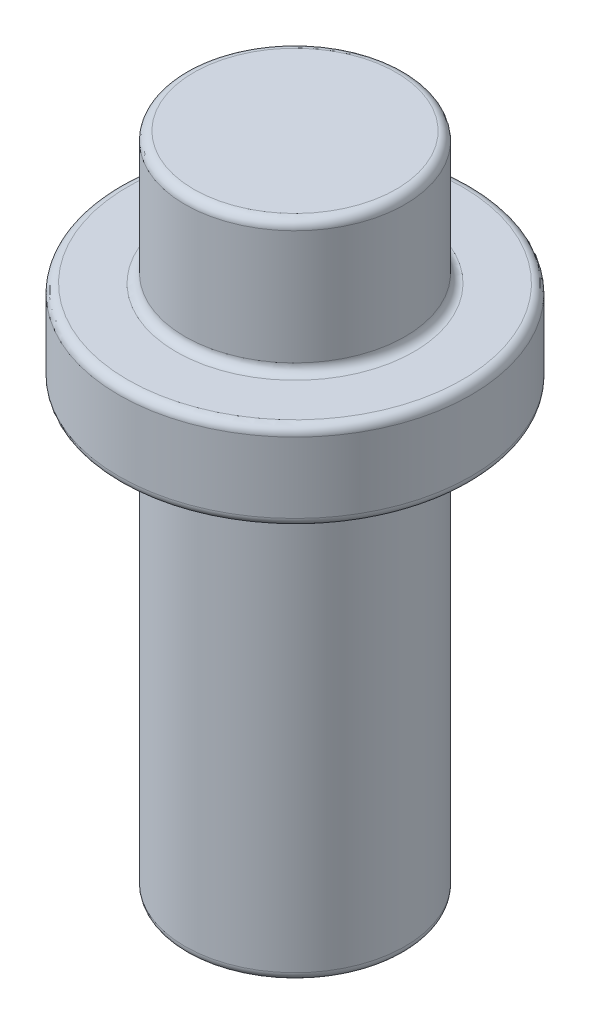
SolidWorks part; units mm, degrees
ref_plane "Front Plane" through (0, 0, 0) normal (0, 0, 1) x (1, 0, 0)
ref_plane "Top Plane" through (0, 0, 0) normal (0, 1, 0) x (1, 0, 0)
ref_plane "Right Plane" through (0, 0, 0) normal (1, 0, 0) x (0, 0, -1)
sketch "Sketch1" plane through (0, 0, 0) normal (0, 1, 0) x (1, 0, 0)
  circle A0 centre (0, 0) radius 2.5
  dimension "D1" = 5
extrude "Boss-Extrude1" add sketch "Sketch1" along normal blind 15 contours A0
ref_plane "Plane1" through (0, 10, 0) normal (0, 1, 0) x (1, 0, 0)
sketch "Sketch2" plane through (0, 10, 0) normal (0, 1, 0) x (1, 0, 0)
  circle A0 centre (0, 0) radius 4
  dimension "D1" = 8
extrude "Boss-Extrude2" add sketch "Sketch2" along normal blind 2 contours A0
fillet "Fillet1" radius 0.2 6 edges at (0, 0, 2.5) (0, 12, 4) (0, 10, 4) (0, 10, 2.5) (0, 12, 2.5) (0, 15, 2.5)
